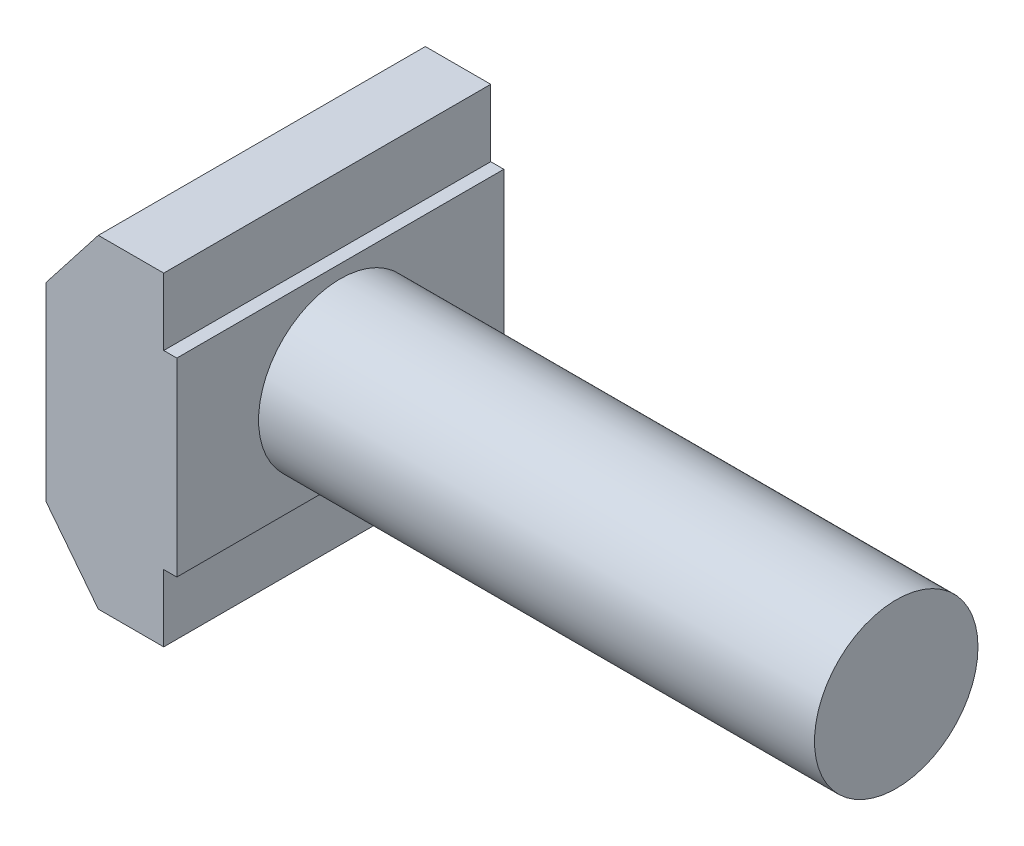
SolidWorks part; units mm, degrees
material "AISI 304"
ref_plane "Front Plane" through (0, 0, 0) normal (0, 0, 1) x (1, 0, 0)
ref_plane "Top Plane" through (0, 0, 0) normal (0, 1, 0) x (1, 0, 0)
ref_plane "Right Plane" through (0, 0, 0) normal (1, 0, 0) x (0, 0, -1)
sketch "Sketch1" plane through (0, 0, 0) normal (0, 0, 1) x (1, 0, 0)
  line L0 (-34.9872, 0) -> (34.9872, 0) construction
  line L1 (0, -25.4818) -> (0, 25.4818) construction
  line L2 (0, -2.9) -> (0, 2.9)
  line L3 (0, -2.9) -> (-0.4, -2.9)
  line L4 (-0.4, -2.9) -> (-0.4, -4.95)
  line L5 (-4, -2.9) -> (-4, 2.9) construction
  line L6 (-0.4, -4.95) -> (-2.4, -4.95)
  line L7 (-2.4, -4.95) -> (-4, -2.9)
  line L8 (-4, -2.9) -> (-4, 2.9)
  line L9 (-2.4, 4.95) -> (-4, 2.9)
  line L10 (-0.4, 4.95) -> (-2.4, 4.95)
  line L11 (-0.4, 2.9) -> (-0.4, 4.95)
  line L12 (0, 2.9) -> (-0.4, 2.9)
  point P0 (-4, 0)
  point P4 (0, 0)
  point P8 (0, 0)
  point P11 (0, 0)
  point P16 (-4, 0)
  dimension "D1" = 5.8
  dimension "D2" = 0.4
  dimension "D3" = 2.05
  dimension "D4" = 4
  dimension "D5" = 2
extrude "Boss-Extrude1" add sketch "Sketch1" along normal mid plane 10
sketch "Sketch2" plane through (0, 0, 0) normal (1, 0, 0) x (0, 0, -1)
  line L0 (-32.2457, 0) -> (32.2457, 0) construction
  line L1 (0, -27.4905) -> (0, 27.4905) construction
  circle A0 centre (0, 0) radius 2.5
  point P4 (0, 0)
  point P8 (0, 0)
  dimension "D1" = 5
extrude "Boss-Extrude2" add sketch "Sketch2" along normal blind 17
thread "Thread1" pitch 0.8 start angle 0, offset 0, length 0, pitch 0.8, diameter 5
ref_plane "Plane1" through (17, 0, 2.5) normal (0, -1, 0) x (0, 0, 1)
sketch "Thread Profile1" plane through (17, 0, 2.5) normal (0, -1, 0) x (0, 0, 1)
  line L0 (0, 0) -> (0, 0.8) construction
  line L11 (0, 0) -> (0, 0.7)
  line L12 (0, 0.7) -> (-0.433, 0.45)
  line L13 (-0.433, 0.45) -> (-0.433, 0.25)
  line L15 (-0.433, 0.25) -> (0, 0)
  line L17 (-0.433, 0.35) -> (0, 0.35) construction
  point P2 (0, 0)
  dimension "Pitch" = 0.8
  dimension "Profile_Angle" = 60
  dimension "Profile_Land" = 0.2
  dimension "Profile_Height" = 0.433
